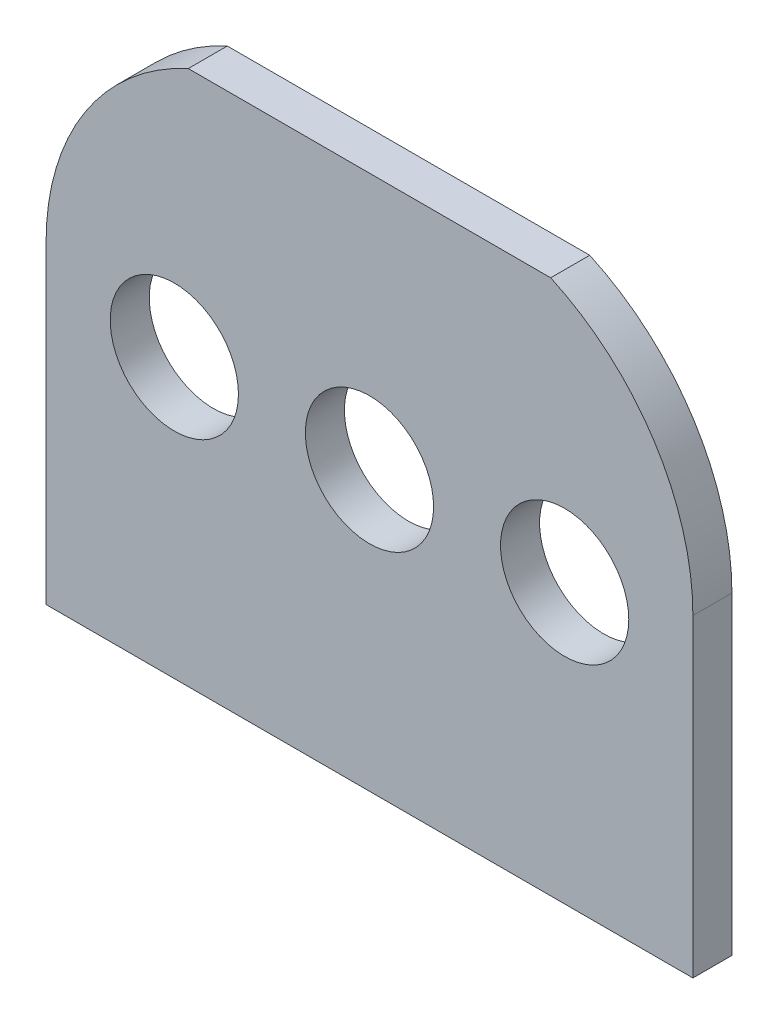
SolidWorks part; units mm, degrees
ref_plane "Płaszczyzna przednia" through (0, 0, 0) normal (0, 0, 1) x (1, 0, 0)
ref_plane "Płaszczyzna górna" through (0, 0, 0) normal (0, 1, 0) x (1, 0, 0)
ref_plane "Płaszczyzna prawa" through (0, 0, 0) normal (1, 0, 0) x (0, 0, -1)
sketch "Szkic1" plane through (0, 0, 0) normal (0, 0, 1) x (1, 0, 0)
  line L0 (-5.8, -4.9941) -> (5.8, -4.9941)
  line L1 (5.8, -4.9941) -> (5.8, 0.6349)
  line L2 (3.25, 4.6059) -> (-3.25, 4.6059)
  line L3 (-5.8, 0.6349) -> (-5.8, -4.9941)
  line L4 (0, -22.1425) -> (0, 47.2243) construction
  arc A0 (5.8, 0.6349) -> (3.25, 4.6059) centre (1.4331, 0.6349) ccw
  arc A1 (-3.25, 4.6059) -> (-5.8, 0.6349) centre (-1.4331, 0.6349) ccw
  circle A2 centre (0, 0) radius 1.15
  circle A3 centre (3.5, 0) radius 1.15
  circle A4 centre (-3.5, 0) radius 1.15
  point P8 (0, -4.9941)
  dimension "D4" = 2.3
  dimension "D6" = 3.5
  dimension "D1" = 6.5
  dimension "D2" = 9.6
  dimension "D3" = 11.6
  dimension "D5" = 3.5
extrude "Dodanie-wyciągnięcie1" add sketch "Szkic1" along normal blind 0.7
